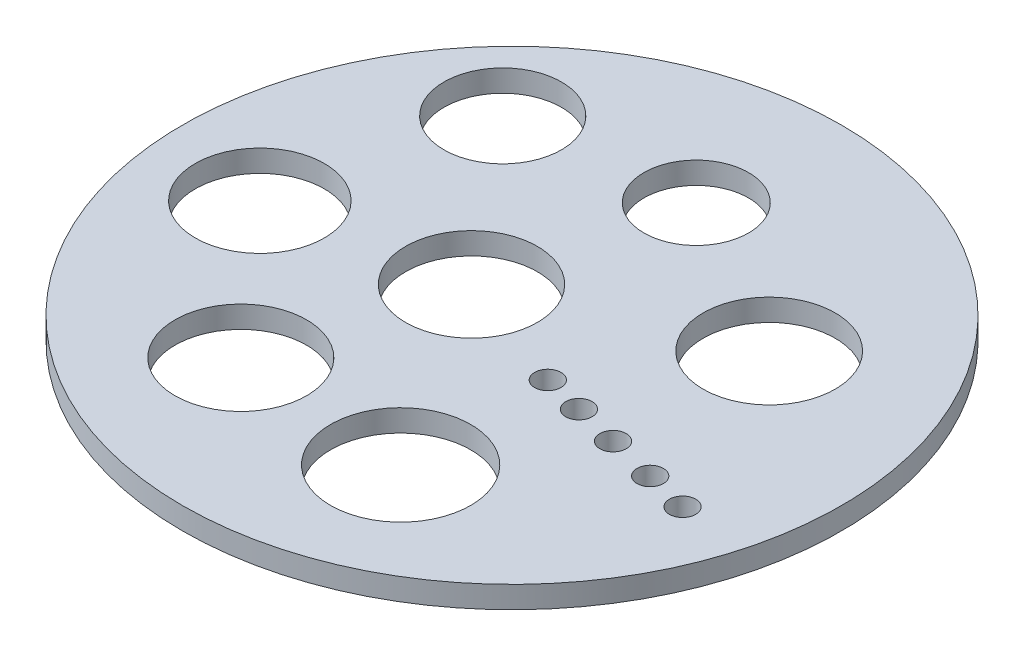
SolidWorks part; units mm, degrees
ref_plane "Front Plane" through (0, 0, 0) normal (0, 0, 1) x (1, 0, 0)
ref_plane "Top Plane" through (0, 0, 0) normal (0, 1, 0) x (1, 0, 0)
ref_plane "Right Plane" through (0, 0, 0) normal (1, 0, 0) x (0, 0, -1)
sketch "Sketch1" plane through (0, 0, 0) normal (0, 1, 0) x (1, 0, 0)
  circle A0 centre (-1.2077, 1.2218) radius 15
  dimension "D1" = 30
extrude "Boss-Extrude1" add sketch "Sketch1" along normal blind 1
sketch "Sketch2" plane through (0, 1, 0) normal (0, 1, 0) x (1, 0, 0)
  line L0 (0, 0) -> (8.2707, -1.9656)
  circle A0 centre (8.2707, -1.9656) radius 0.6
  circle A1 centre (-1.2077, 1.2218) radius 15 construction
  circle A2 centre (6.0522, -1.4384) radius 0.6
  circle A3 centre (4.0149, -0.9542) radius 0.6
  circle A4 centre (2.1554, -0.5123) radius 0.6
  circle A5 centre (10.2205, -2.4432) radius 0.6
  circle A6 centre (6.0522, 5.6677) radius 3.0069
  circle A7 centre (2.1554, -7.2102) radius 3.1917
  circle A8 centre (-1.4506, 9.8514) radius 2.3821
  circle A9 centre (-3.3484, 1.5186) radius 3
  circle A10 centre (-5.7064, -6.6233) radius 2.9954
  circle A11 centre (-9.2802, 8.8718) radius 2.6757
  circle A12 centre (-11.4637, 0) radius 2.9379
  dimension "D2" = 1.2
  dimension "D3" = 1.2
  dimension "D4" = 1.2
  dimension "D5" = 1.2
  dimension "D6" = 1.2
  dimension "D7" = 6
  dimension "D1" = 10
extrude "Cut-Extrude2" cut sketch "Sketch2" against normal through all
